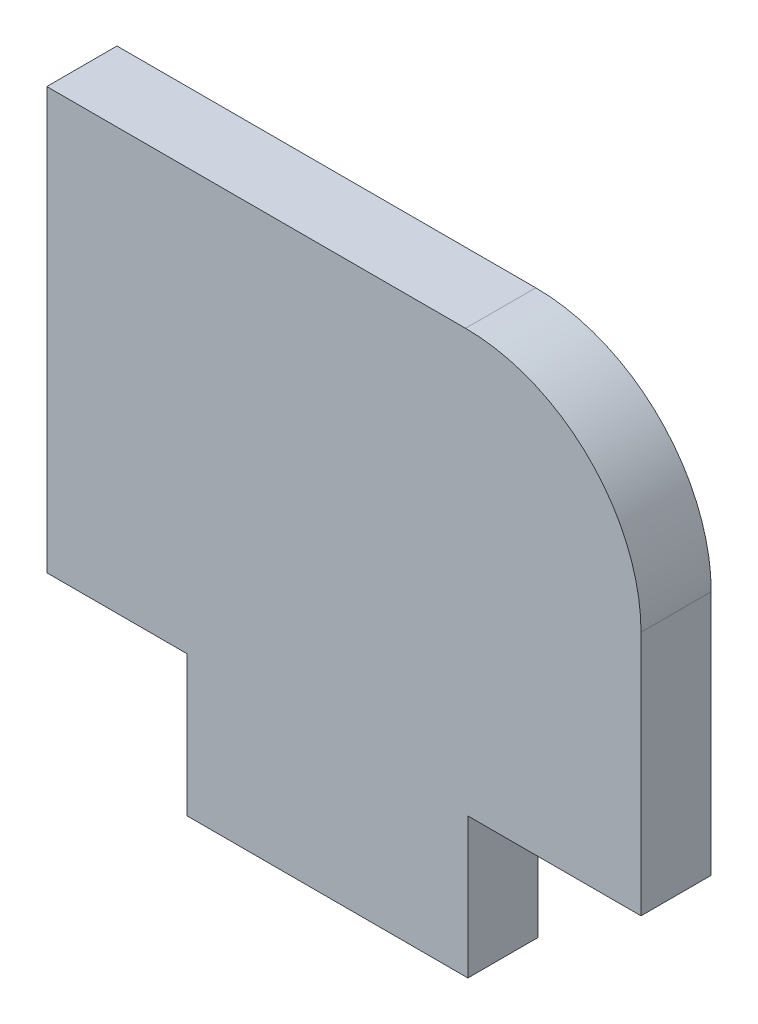
SolidWorks part; units mm, degrees
ref_plane "Front Plane" through (0, 0, 0) normal (0, 0, 1) x (1, 0, 0)
ref_plane "Top Plane" through (0, 0, 0) normal (0, 1, 0) x (1, 0, 0)
ref_plane "Right Plane" through (0, 0, 0) normal (1, 0, 0) x (0, 0, -1)
sketch "Sketch1" plane through (0, 0, 0) normal (0, 0, 1) x (1, 0, 0)
  line L0 (5.5334, -4) -> (10.4666, -4)
  line L1 (-2.4666, -4) -> (-6.4666, -4)
  line L2 (-6.4666, -4) -> (-6.4666, 8)
  line L3 (-6.4666, 8) -> (5.4666, 8)
  line L4 (5.5334, -4) -> (5.5334, -8)
  line L5 (5.5334, -8) -> (-2.4666, -8)
  line L6 (-2.4666, -8) -> (-2.4666, -4)
  line L7 (10.4666, 3) -> (10.4666, -4)
  arc A0 (10.4666, 3) -> (5.4666, 8) centre (5.4666, 3) ccw
  dimension "D1" = 5
  dimension "D2" = 12
  dimension "D3" = 4.9332
  dimension "D4" = 8
  dimension "D5" = 4
extrude "Boss-Extrude1" add sketch "Sketch1" along normal blind 2
